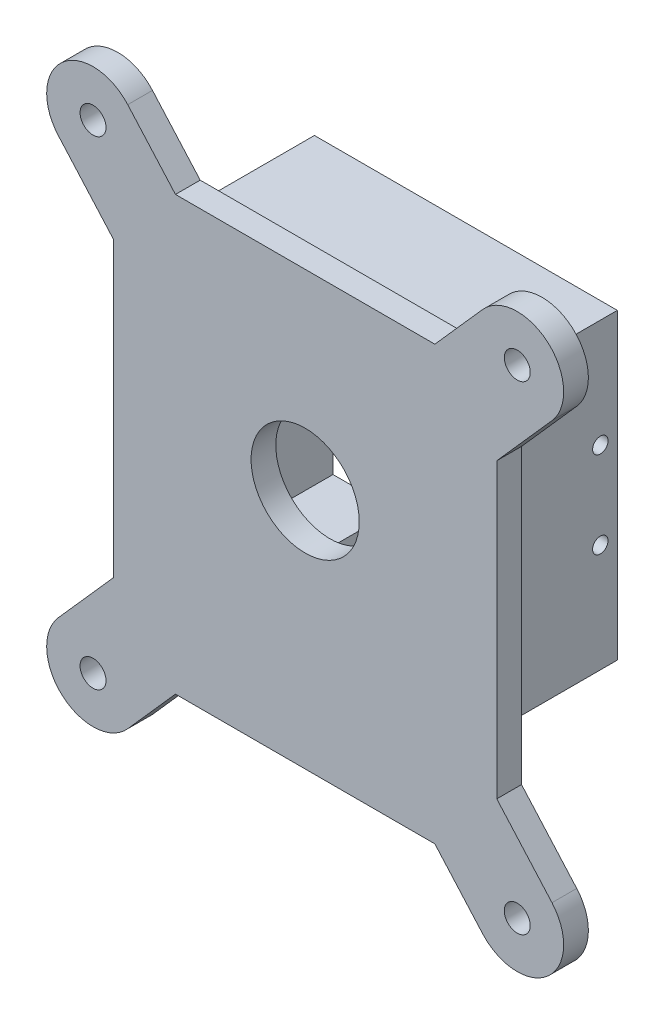
SolidWorks part; units mm, degrees
ref_plane "Front Plane" through (0, 0, 0) normal (0, 0, 1) x (1, 0, 0)
ref_plane "Top Plane" through (0, 0, 0) normal (0, 1, 0) x (1, 0, 0)
ref_plane "Right Plane" through (0, 0, 0) normal (1, 0, 0) x (0, 0, -1)
sketch "Sketch1" plane through (0, 0, 0) normal (0, 0, 1) x (1, 0, 0)
  line L0 (42, 42) -> (0, 42) construction
  line L1 (-10, -18) -> (52, -18)
  line L2 (-10, -18) -> (-10, 52)
  line L3 (-10, 52) -> (52, 52)
  line L4 (52, -18) -> (52, 52)
  line L5 (42, 0) -> (42, 42) construction
  line L7 (32, -8) -> (10, -8) construction
  line L8 (21, 42) -> (21, 0) construction
  line L9 (42, 42) -> (0, 42) construction
  line L10 (0, 0) -> (42, 0) construction
  circle A0 centre (21, 21) radius 8.75
  point P16 (21, 52)
  dimension "D4" = 17.5
  dimension "D1" = 10
  dimension "D2" = 10
  dimension "D3" = 10
extrude "Bottom" add sketch "Sketch1" along normal blind 4
sketch "Sketch2" plane through (0, 0, 0) normal (0, 0, -1) x (-1, 0, 0)
  line L0 (-21, 52) -> (-21, -18) construction
  line L1 (-52, 52) -> (10, 52) construction
  line L2 (10, -18) -> (-52, -18) construction
  circle A0 centre (-37.5, 37.5) radius 2.75 construction
  circle A1 centre (-4.5, 37.5) radius 2.75 construction
  circle A2 centre (-4.5, 4.5) radius 2.75 construction
  circle A3 centre (-15, 4) radius 3.25 construction
  circle A4 centre (-27, 4) radius 3.25 construction
  circle A5 centre (-37.5, 4.5) radius 2.75 construction
  circle A6 centre (-37.5, 37.5) radius 2.75 construction
  circle A7 centre (-4.5, 37.5) radius 2.75 construction
  circle A8 centre (-4.5, 4.5) radius 2.75 construction
  circle A9 centre (-15, 4) radius 3.25 construction
  circle A10 centre (-27, 4) radius 3.25 construction
  circle A11 centre (-37.5, 4.5) radius 2.75 construction
  circle A12 centre (-37.5, 4.5) radius 3.25
  circle A13 centre (-37.5, 37.5) radius 3.25
  circle A14 centre (-27, 4) radius 3.75
  circle A15 centre (-15, 4) radius 3.75
  circle A16 centre (-4.5, 4.5) radius 3.25
  circle A17 centre (-4.5, 37.5) radius 3.25
  dimension "D1" = 5.5
  dimension "D2" = 6.5
  dimension "D3" = 6.5
  dimension "D4" = 6.5
  dimension "D5" = 7.5
  dimension "D6" = 6.5
  dimension "D7" = 6.5
  dimension "D8" = 7.5
extrude "Screw_inlets" cut sketch "Sketch2" against normal blind 2.3
sketch "Sketch3" plane through (0, 0, 0) normal (0, 0, -1) x (-1, 0, 0)
  line L0 (10.0124, 52.014) -> (-51.9876, -17.986) construction
  line L1 (10, 40.6884) -> (18.9296, 50.7702)
  line L2 (10, 52) -> (10, -18) construction
  line L3 (18.9296, 50.7702) -> (7.7008, 60.7157) construction
  line L4 (7.7008, 60.7157) -> (-0.0189, 52)
  line L5 (-52, 52) -> (10, 52) construction
  line L6 (-0.0189, 52) -> (10, 52)
  line L7 (10, 52) -> (10, 40.6884)
  line L8 (-21, 52) -> (-21, -18) construction
  line L9 (10, -18) -> (-52, -18) construction
  line L10 (-52, 17) -> (10, 17) construction
  line L11 (-52, -18) -> (-52, 52) construction
  line L12 (-52, 40.6884) -> (-60.9296, 50.7702)
  line L13 (-52, 52) -> (-52, 40.6884)
  line L14 (-41.9811, 52) -> (-52, 52)
  line L15 (-49.7008, 60.7157) -> (-41.9811, 52)
  line L16 (10, -6.6884) -> (18.9296, -16.7702)
  line L17 (10, -18) -> (10, -6.6884)
  line L18 (-0.0189, -18) -> (10, -18)
  line L19 (7.7008, -26.7157) -> (-0.0189, -18)
  line L20 (-52, -18) -> (-52, -6.6884)
  line L21 (-41.9811, -18) -> (-52, -18)
  line L22 (-49.7008, -26.7157) -> (-41.9811, -18)
  line L23 (-52, -6.6884) -> (-60.9296, -16.7702)
  arc A0 (18.9296, 50.7702) -> (7.7008, 60.7157) centre (13.3152, 55.7429) ccw
  circle A1 centre (13.3152, 55.7429) radius 2.1
  circle A2 centre (-55.3152, 55.7429) radius 2.1
  arc A3 (-60.9296, 50.7702) -> (-49.7008, 60.7157) centre (-55.3152, 55.7429) cw
  arc A4 (18.9296, -16.7702) -> (7.7008, -26.7157) centre (13.3152, -21.7429) cw
  circle A5 centre (13.3152, -21.7429) radius 2.1
  circle A6 centre (-55.3152, -21.7429) radius 2.1
  arc A7 (-60.9296, -16.7702) -> (-49.7008, -26.7157) centre (-55.3152, -21.7429) ccw
  point P8 (13.3152, 55.7429)
  dimension "D1" = 15
  dimension "D3" = 4.2
  dimension "D2" = 5
extrude "Mounting_arms" add sketch "Sketch3" against normal up to surface (4 mm away) up to face at (21, 17, 4)
sketch "Sketch4" plane through (0, 0, 0) normal (0, 0, -1) x (-1, 0, 0)
  line L0 (-42, 0) -> (-42, 42) construction
  line L1 (-42.5, 42.5) -> (0.5, 42.5)
  line L2 (-42.5, 42.5) -> (-42.5, -0.5)
  line L3 (-32.5, -8.5) -> (-9.5, -8.5)
  line L4 (0.5, 42.5) -> (0.5, -0.5)
  line L5 (-42, 42) -> (0, 42) construction
  line L6 (-21, -18) -> (-21, 52) construction
  line L7 (-0.0189, -18) -> (-41.9811, -18) construction
  line L8 (-41.9811, 52) -> (-0.0189, 52) construction
  line L9 (-32.5, -8.5) -> (-32.5, -0.5)
  line L10 (-32.5, -0.5) -> (-42.5, -0.5)
  line L11 (-9.5, -0.5) -> (0.5, -0.5)
  line L12 (-9.5, -8.5) -> (-9.5, -0.5)
  line L13 (0, 0) -> (-42, 0) construction
  line L14 (-32, -8) -> (-32, 0) construction
  line L15 (-32, -8) -> (-10, -8) construction
  point P14 (-21, 42.5)
  dimension "D1" = 0.5
  dimension "D2" = 0.5
  dimension "D3" = 0.5
  dimension "D4" = 0.5
  dimension "D5" = 0.5
extrude "Walls" add sketch "Sketch4" along normal offset from surface (22 mm away) 5 thin thin type one direction wall 3
sketch "Sketch5" plane through (0, -11.5, 0) normal (0, -1, 0) x (1, 0, 0)
  circle A0 centre (21, -8.5) radius 3.125 construction
  circle A1 centre (21, -8.5) radius 3.125 construction
  circle A2 centre (21, -8.5) radius 4
  dimension "D2" = 8
extrude "Adapter_bolt_hole" cut sketch "Sketch5" against normal up to next
sketch "Sketch7" plane through (45.5, 0, 0) normal (1, 0, 0) x (0, 0, -1)
  line L0 (22, 21) -> (0, 21) construction
  line L1 (22, 45.5) -> (22, -3.5) construction
  line L2 (0, 45.5) -> (0, -3.5) construction
  line L3 (17, 0) -> (17, 42) construction
  line L4 (18, 0) -> (18, 42) construction
  line L5 (0, 42) -> (17, 42) construction
  line L6 (0, 0) -> (17, 0) construction
  circle A0 centre (19.25, 28) radius 1.25
  circle A1 centre (19.25, 14) radius 1.25
  dimension "D2" = 2.5
  dimension "D1" = 7
  dimension "D3" = 1
extrude "M2_lock_holes" cut sketch "Sketch7" against normal up to surface (49 mm away) up to face at (-3.5, 21, -11)
